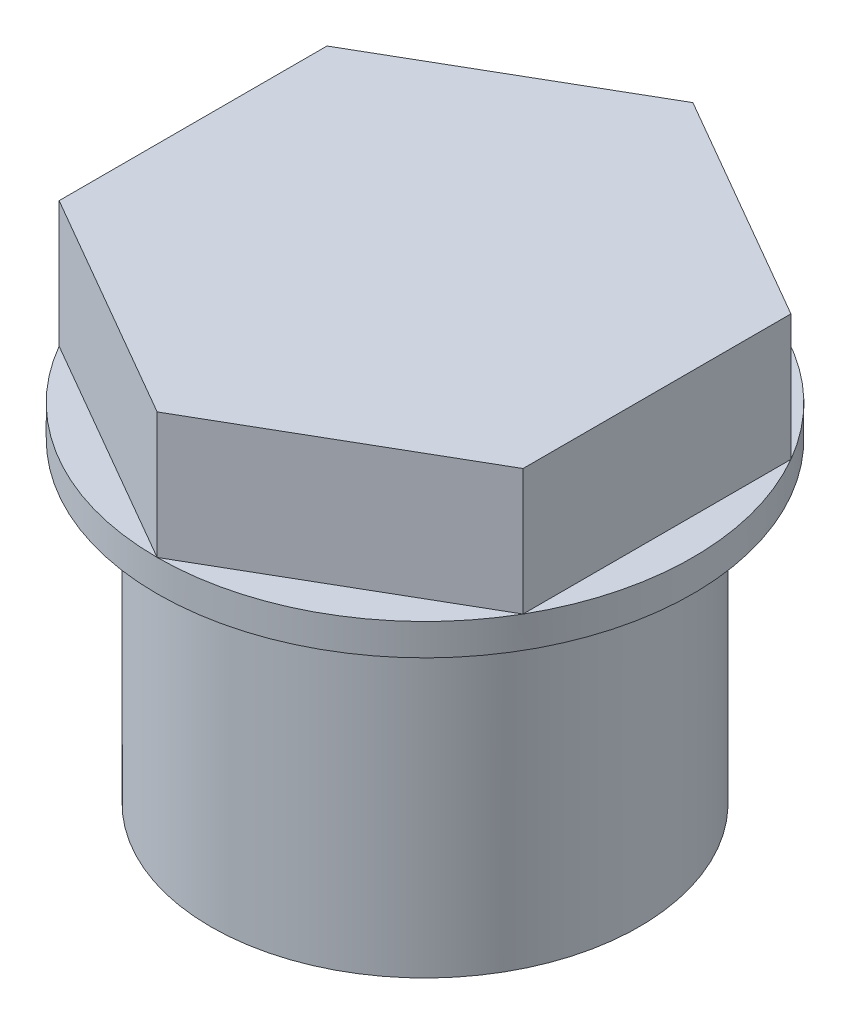
SolidWorks part; units mm, degrees
ref_plane "Front" through (0, 0, 0) normal (0, 0, 1) x (1, 0, 0)
ref_plane "Top" through (0, 0, 0) normal (0, 1, 0) x (1, 0, 0)
ref_plane "Right" through (0, 0, 0) normal (1, 0, 0) x (0, 0, -1)
sketch "Sketch1" plane through (0, 0, 0) normal (0, 1, 0) x (1, 0, 0)
  circle A0 centre (0, 0) radius 8.5
  dimension "D1" = 17
extrude "Extrude1" add sketch "Sketch1" along normal blind 1
sketch "Sketch2" plane through (0, 1, 0) normal (0, 1, 0) x (1, 0, 0)
  line L0 (0, 8.5) -> (-7.3612, 4.25)
  line L1 (-7.3612, 4.25) -> (-7.3612, -4.25)
  line L2 (-7.3612, -4.25) -> (0, -8.5)
  line L3 (0, -8.5) -> (7.3612, -4.25)
  line L4 (7.3612, -4.25) -> (7.3612, 4.25)
  line L5 (7.3612, 4.25) -> (0, 8.5)
  circle A0 centre (0, 0) radius 8.5 construction
extrude "Extrude2" add sketch "Sketch2" along normal blind 4
sketch "Sketch3" plane through (0, 0, 0) normal (0, -1, 0) x (1, 0, 0)
  circle A0 centre (0, 0) radius 6.8
  dimension "D1" = 13.6
extrude "Extrude3" add sketch "Sketch3" along normal blind 10
